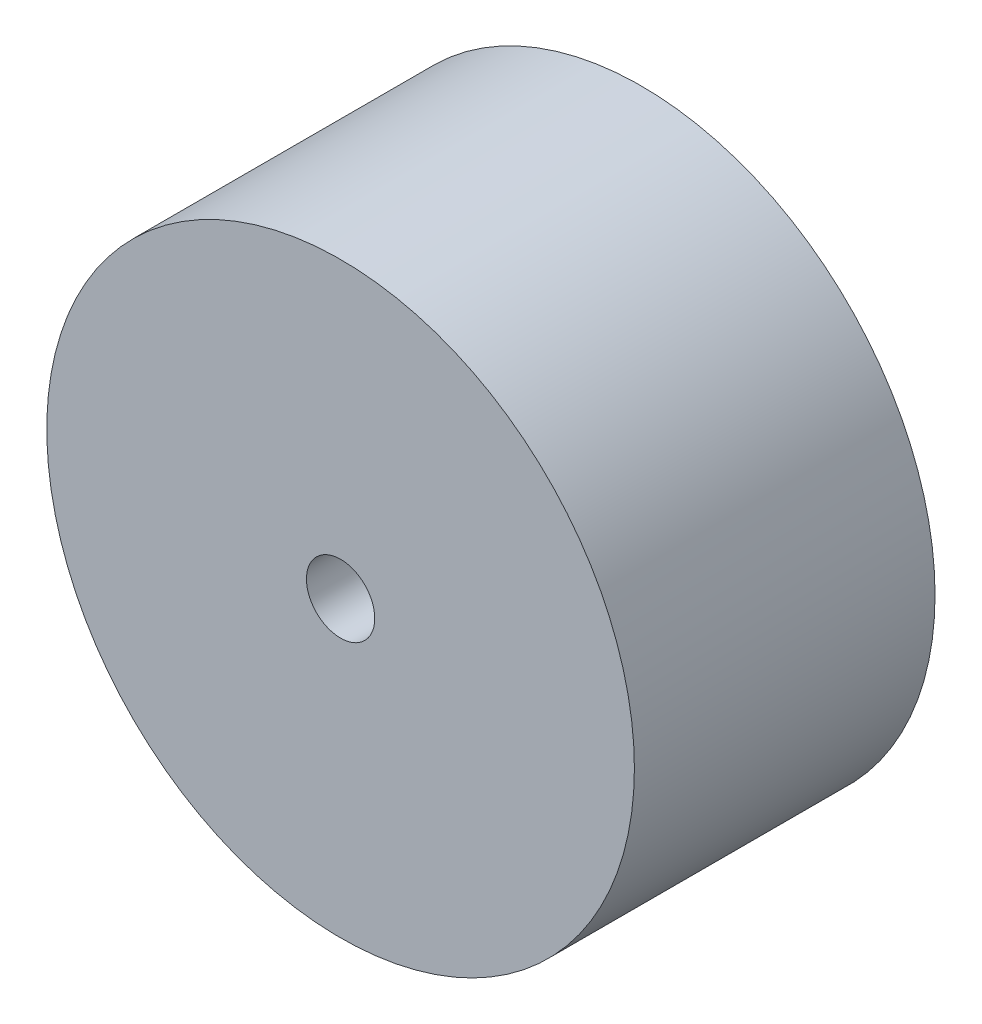
SolidWorks part; units mm, degrees
ref_plane "Front Plane" through (0, 0, 0) normal (0, 0, 1) x (1, 0, 0)
ref_plane "Top Plane" through (0, 0, 0) normal (0, 1, 0) x (1, 0, 0)
ref_plane "Right Plane" through (0, 0, 0) normal (1, 0, 0) x (0, 0, -1)
sketch "Sketch1" plane through (0, 0, 0) normal (0, 0, 1) x (1, 0, 0)
  circle A0 centre (0, 0) radius 21.5
  circle A1 centre (0, 0) radius 2.5
  dimension "D1" = 43
  dimension "D2" = 5
extrude "Boss-Extrude1" add sketch "Sketch1" along normal blind 22
